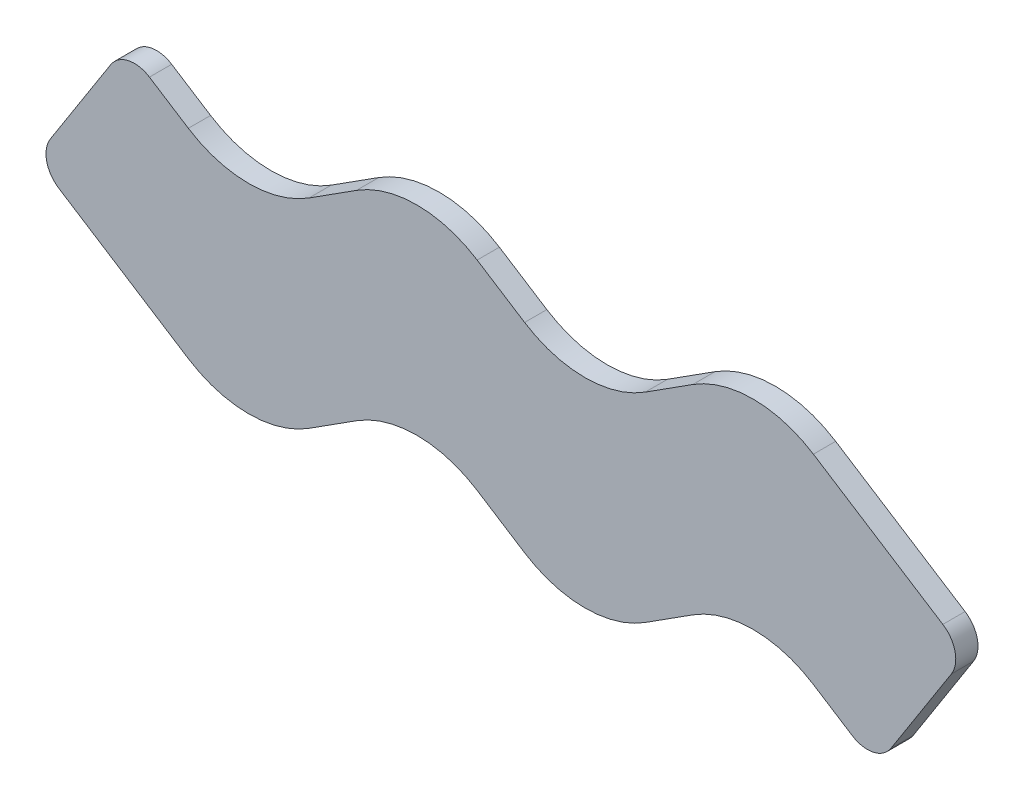
SolidWorks part; units mm, degrees
material "3003-H14"
ref_plane "X-Y Datum" through (0, 0, 0) normal (0, 0, 1) x (1, 0, 0)
ref_plane "X-Z Datum" through (0, 0, 0) normal (0, 1, 0) x (1, 0, 0)
ref_plane "Y-Z Datum" through (0, 0, 0) normal (1, 0, 0) x (0, 0, -1)
sketch "Sketch3" plane through (0, 0, 0) normal (0, 0, 1) x (1, 0, 0)
  line L0 (10.775, 10.775) -> (22.775, 33.775) construction
  line L1 (0, 0) -> (156.4633, 0) construction
  line L2 (0, 0) -> (0, 56.3098) construction
  line L3 (0, 56.3098) -> (156.4633, 56.3098) construction
  line L4 (156.4633, 0) -> (156.4633, 56.3098) construction
  line L5 (34.775, 10.775) -> (46.775, 33.775) construction
  line L6 (58.775, 10.775) -> (70.775, 33.775) construction
  line L7 (16.775, 22.275) -> (64.775, 22.275) construction
  line L8 (34.775, 10.775) -> (22.775, 33.775) construction
  line L9 (46.775, 33.775) -> (58.775, 10.775) construction
  line L10 (10.775, 10.775) -> (34.775, 10.775) construction
  line L11 (58.775, 10.775) -> (34.775, 10.775) construction
  line L12 (22.775, 33.775) -> (46.775, 33.775) construction
  line L13 (70.775, 33.775) -> (46.775, 33.775) construction
  line L14 (22.775, 33.775) -> (22.775, 10.775) construction
  line L15 (46.775, 10.775) -> (46.775, 33.775) construction
  line L16 (34.775, 10.775) -> (34.775, 33.775) construction
  line L17 (58.775, 33.775) -> (58.775, 10.775)
  line L18 (16.775, 22.275) -> (22.775, 18.4417)
  line L19 (46.775, 33.775) -> (37.6949, 27.9739)
  line L20 (34.775, 10.775) -> (43.8551, 16.5761)
  line L21 (46.775, 18.4417) -> (34.775, 26.1083)
  line L22 (16.775, 22.275) -> (10.775, 26.1083)
  line L23 (46.775, 33.775) -> (55.8551, 27.9739)
  line L24 (52.775, 22.275) -> (58.775, 26.1083)
  line L25 (64.775, 22.275) -> (70.775, 18.4417)
  line L26 (25.6949, 16.5761) -> (34.775, 10.775)
  line L27 (34.775, 26.1083) -> (22.775, 18.4417)
  line L28 (46.775, 18.4417) -> (52.775, 22.275)
  line L29 (58.775, 26.1083) -> (64.775, 22.275)
  line L30 (68.0053, 27.3312) -> (74.0053, 23.4978)
  line L31 (58.775, 33.2283) -> (68.0053, 27.3312)
  line L32 (49.5447, 27.3312) -> (58.775, 33.2283)
  line L33 (46.775, 25.5617) -> (49.5447, 27.3312)
  line L34 (46.775, 25.5617) -> (34.775, 33.2283)
  line L35 (34.775, 33.2283) -> (22.775, 25.5617)
  line L36 (20.0053, 27.3312) -> (22.775, 25.5617)
  line L37 (20.0053, 27.3312) -> (14.0053, 31.1645)
  line L38 (13.5447, 17.2188) -> (7.5447, 21.0522)
  line L39 (13.5447, 17.2188) -> (22.775, 11.3217)
  line L40 (34.775, 18.9883) -> (22.775, 11.3217)
  line L41 (46.775, 11.3217) -> (34.775, 18.9883)
  line L42 (46.775, 11.3217) -> (56.0053, 17.2188)
  line L43 (56.0053, 17.2188) -> (58.775, 18.9883)
  line L44 (58.775, 18.9883) -> (61.5447, 17.2188)
  line L45 (61.5447, 17.2188) -> (67.5447, 13.3855)
  line L46 (67.5447, 13.3855) -> (74.0053, 23.4978)
  line L47 (7.5447, 21.0522) -> (14.0053, 31.1645)
  line L48 (58.775, 10.775) -> (70.775, 10.775) construction
  line L49 (70.775, 10.775) -> (70.775, 33.775)
  circle A0 centre (10.775, 10.775) radius 10.775 construction
  circle A1 centre (34.775, 10.775) radius 10.775 construction
  circle A2 centre (22.775, 33.775) radius 10.775 construction
  circle A3 centre (46.775, 33.775) radius 10.775 construction
  circle A4 centre (70.775, 33.775) radius 10.775 construction
  circle A5 centre (58.775, 10.775) radius 10.775 construction
  circle A6 centre (10.775, 10.775) radius 4.7 construction
  circle A7 centre (34.775, 10.775) radius 4.7 construction
  circle A8 centre (58.775, 10.775) radius 4.7 construction
  circle A9 centre (70.775, 33.775) radius 4.7 construction
  circle A10 centre (46.775, 33.775) radius 4.7 construction
  circle A11 centre (22.775, 33.775) radius 4.7 construction
  circle A18 centre (130.775, 10.775) radius 10.775 construction
  circle A19 centre (106.775, 10.775) radius 10.775 construction
  circle A20 centre (82.775, 10.775) radius 10.775 construction
  circle A21 centre (94.775, 33.775) radius 10.775 construction
  circle A22 centre (118.775, 33.775) radius 10.775 construction
  circle A23 centre (142.775, 33.775) radius 10.775 construction
  dimension "D1" = 21.55
  dimension "D9" = 9.4
  dimension "D2" = 24
  dimension "D3" = 23
  dimension "D4" = 12
  dimension "D6" = 24
  dimension "D8" = 24
  dimension "D10" = 6
  dimension "D11" = 6
  dimension "D5" = 6
  dimension "D7" = 5
extrude "Boss-Extrude1" add sketch "Sketch3" along normal blind 1.5875
ref_plane "Plane1" through (70.775, 0, 0) normal (1, 0, 0) x (0, 0, -1)
mirror "Mirror1" [suppressed] about plane through (70.775, 0, 0) normal (1, 0, 0)
sketch "Sketch4" plane through (0, 0, 1.5875) normal (0, 0, 1) x (1, 0, 0)
  line L0 (67.5447, 13.3855) -> (70.775, 11.3217)
  line L1 (70.775, 11.3217) -> (74.0053, 13.3855)
  line L24 (46.775, 11.3217) -> (58.775, 18.9883)
  line L25 (58.775, 18.9883) -> (67.5447, 13.3855)
  line L26 (67.5447, 13.3855) -> (74.0053, 23.4978)
  line L39 (74.0053, 23.4978) -> (58.775, 33.2283)
  line L40 (58.775, 33.2283) -> (46.775, 25.5617)
  line L41 (46.775, 25.5617) -> (34.775, 33.2283)
  line L42 (34.775, 33.2283) -> (22.775, 25.5617)
  line L43 (22.775, 25.5617) -> (14.0053, 31.1645)
  line L44 (14.0053, 31.1645) -> (7.5447, 21.0522)
  line L45 (7.5447, 21.0522) -> (22.775, 11.3217)
  line L46 (22.775, 11.3217) -> (34.775, 18.9883)
  line L47 (34.775, 18.9883) -> (46.775, 11.3217)
  line L48 (46.775, 11.3217) -> (58.775, 18.9883)
  line L49 (58.775, 18.9883) -> (67.5447, 13.3855)
  line L50 (67.5447, 13.3855) -> (74.0053, 23.4978)
  line L63 (74.0053, 23.4978) -> (58.775, 33.2283)
  line L64 (58.775, 33.2283) -> (46.775, 25.5617)
  line L65 (46.775, 25.5617) -> (34.775, 33.2283)
  line L66 (34.775, 33.2283) -> (22.775, 25.5617)
  line L67 (22.775, 25.5617) -> (14.0053, 31.1645)
  line L68 (14.0053, 31.1645) -> (7.5447, 21.0522)
  line L69 (7.5447, 21.0522) -> (22.775, 11.3217)
  line L70 (22.775, 11.3217) -> (34.775, 18.9883)
  line L71 (34.775, 18.9883) -> (46.775, 11.3217)
  dimension "D1" = 0
extrude "Boss-Extrude2" [suppressed] add sketch "Sketch4" against normal up to surface (1.5875 mm away)
fillet "Fillet1" radius 2 4 edges at (14.0053, 31.1645, 0.7937) (7.5447, 21.0522, 0.7937) (67.5447, 13.3855, 0.7937) (74.0053, 23.4978, 0.7937)
fillet "Fillet2" [suppressed] radius 2
fillet "Fillet3" radius 8 4 edges at (58.775, 33.2283, 0.7937) (46.775, 11.3217, 0.7937) (34.775, 33.2283, 0.7937) (22.775, 11.3217, 0.7937)
fillet "Fillet4" radius 8 4 edges at (58.775, 18.9883, 0.7937) (34.775, 18.9883, 0.7937) (46.775, 25.5617, 0.7937) (22.775, 25.5617, 0.7937)
fillet "Fillet5" [suppressed] radius 8
